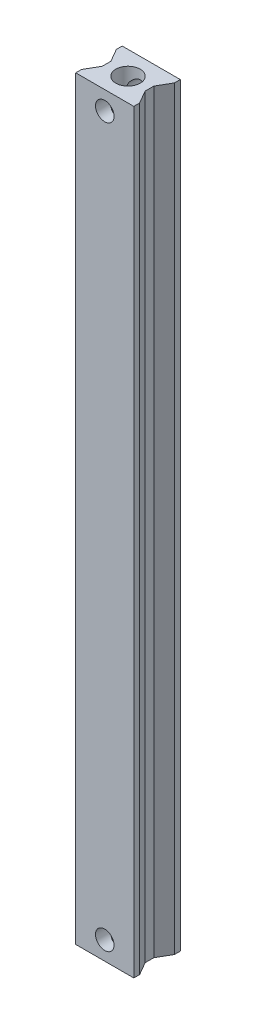
SolidWorks part; units mm, degrees
ref_plane "前视基准面" through (0, 0, 0) normal (0, 0, 1) x (1, 0, 0)
ref_plane "上视基准面" through (0, 0, 0) normal (0, 1, 0) x (1, 0, 0)
ref_plane "右视基准面" through (0, 0, 0) normal (1, 0, 0) x (0, 0, -1)
sketch "草图1" plane through (0, 0, 0) normal (0, 1, 0) x (1, 0, 0)
  line L0 (5, 3.235) -> (-5, 3.235)
  line L1 (-5, 3.235) -> (-5, 2.235)
  line L2 (-5, 2.235) -> (-3.7, -0.0166)
  line L3 (-3.7, -0.0166) -> (-3.7, -1.5166)
  line L4 (-6.4181, -0.7666) -> (10.1337, -0.7666) construction
  line L5 (-5, -3.7683) -> (-3.7, -1.5166)
  line L6 (-5, -4.7683) -> (-5, -3.7683)
  line L7 (5, -4.7683) -> (-5, -4.7683)
  line L8 (0, 3.235) -> (0, -5.1711) construction
  line L9 (5, -4.7683) -> (5, -3.7683)
  line L10 (5, -3.7683) -> (3.7, -1.5166)
  line L11 (3.7, -0.0166) -> (3.7, -1.5166)
  line L12 (5, 2.235) -> (3.7, -0.0166)
  line L13 (5, 3.235) -> (5, 2.235)
  circle A1 centre (0, -0.7666) radius 2.1
  point P1 (-3.7, -0.7666)
  point P17 (0, -4.7683)
  point P22 (3.7, -0.7666)
  dimension "D1" = 1.3
  dimension "D6" = 4.2
  dimension "D2" = 1.5
  dimension "D3" = 60
  dimension "D4" = 1
  dimension "D5" = 10
  dimension "D7" = 7.4
extrude "凸台-拉伸1" add sketch "草图1" along normal blind 130
sketch "草图2" plane through (0, 0, -3.235) normal (0, 0, -1) x (-1, 0, 0)
  line L0 (-5, 130) -> (5, 130) construction
  line L1 (5, 65) -> (-8.8045, 65) construction
  line L2 (5, 130) -> (5, 0) construction
  circle A0 centre (0, 126.8) radius 1.6
  circle A1 centre (0, 3.2) radius 1.6
  dimension "D1" = 3.2
  dimension "D2" = 3.2
extrude "切除-拉伸1" cut sketch "草图2" against normal blind 10
